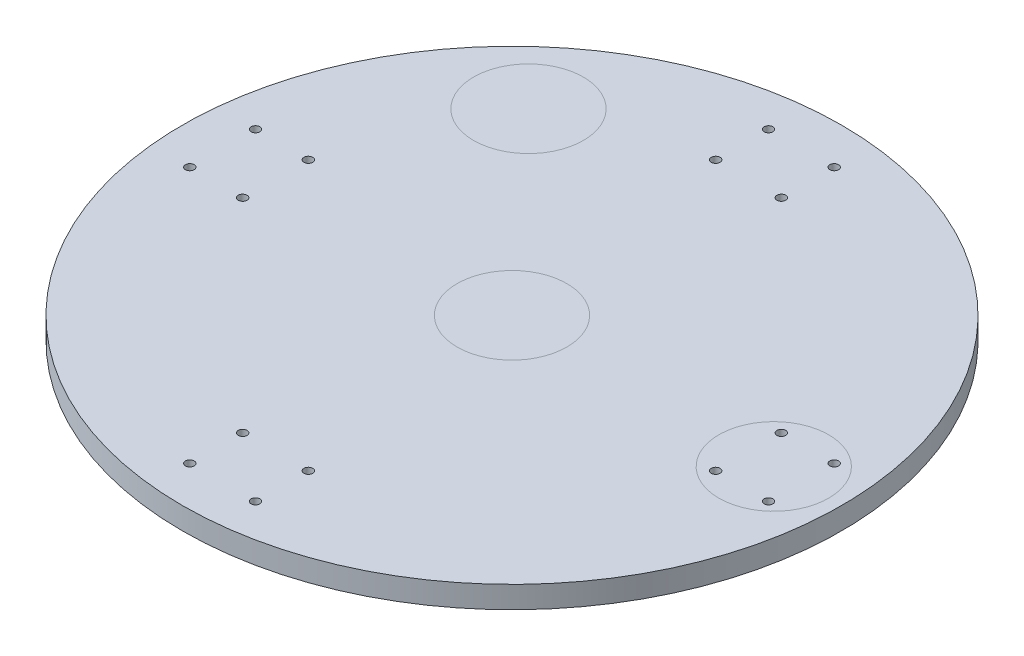
SolidWorks part; units mm, degrees
material "Acrylic"
ref_plane "Front Plane" through (0, 0, 0) normal (0, 0, 1) x (1, 0, 0)
ref_plane "Top Plane" through (0, 0, 0) normal (0, 1, 0) x (1, 0, 0)
ref_plane "Right Plane" through (0, 0, 0) normal (1, 0, 0) x (0, 0, -1)
sketch "Sketch1" plane through (0, 0, 0) normal (0, 1, 0) x (1, 0, 0)
  circle A0 centre (0, 0) radius 150
extrude "Boss-Extrude1" add sketch "Sketch1" along normal blind 10
sketch "Sketch2" plane through (0, 10, 0) normal (0, 1, 0) x (1, 0, 0)
  line L0 (0, 0) -> (-177.8464, 0) construction
  line L1 (0, 0) -> (0, 145.1898) construction
  line L2 (0, 0) -> (115.5258, 115.5258) construction
  circle A0 centre (-14.945, 131.7064) radius 2
  circle A1 centre (-14.945, 107.6464) radius 2
  circle A2 centre (14.945, 107.6464) radius 2
  circle A3 centre (14.945, 131.7064) radius 2
  circle A4 centre (131.7064, 14.945) radius 2
  circle A5 centre (131.7064, -14.945) radius 2
  circle A6 centre (107.6464, -14.945) radius 2
  circle A7 centre (107.6464, 14.945) radius 2
  circle A8 centre (14.945, -131.7064) radius 2
  circle A9 centre (-14.945, -131.7064) radius 2
  circle A10 centre (-14.945, -107.6464) radius 2
  circle A11 centre (14.945, -107.6464) radius 2
  circle A12 centre (-131.7064, -14.945) radius 2
  circle A13 centre (-131.7064, 14.945) radius 2
  circle A14 centre (-107.6464, 14.945) radius 2
  circle A15 centre (-107.6464, -14.945) radius 2
  point P39 (0, 0)
  point P49 (0, 0)
  dimension "D1" = 14.945
  dimension "D2" = 4
  dimension "D3" = 24.06
  dimension "D4" = 4
extrude "Cut-Extrude1" cut sketch "Sketch2" against normal blind 10
sketch "Sketch3" plane through (0, 10, 0) normal (0, 1, 0) x (1, 0, 0)
  circle A0 centre (0, 0) radius 25
  circle A1 centre (-77.6699, 85.1721) radius 25
  circle A2 centre (119.1527, 0) radius 25
split line "Split Line1"
